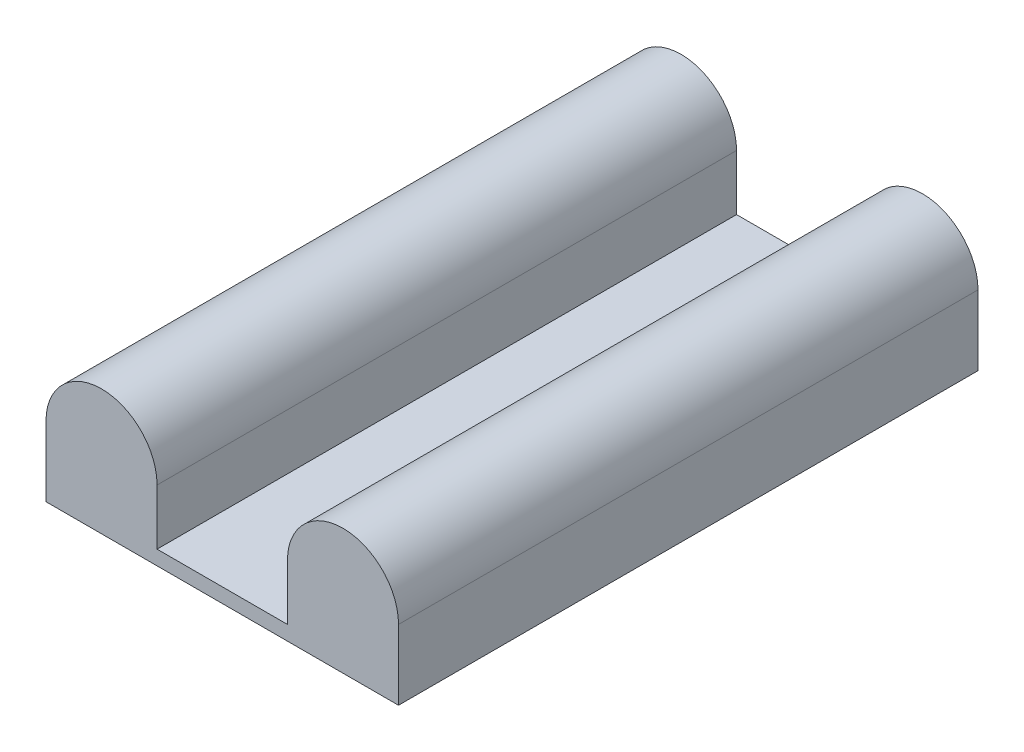
SolidWorks part; units mm, degrees
ref_plane "Front Plane" through (0, 0, 0) normal (0, 0, 1) x (1, 0, 0)
ref_plane "Top Plane" through (0, 0, 0) normal (0, 1, 0) x (1, 0, 0)
ref_plane "Right Plane" through (0, 0, 0) normal (1, 0, 0) x (0, 0, -1)
sketch "Sketch1" plane through (0, 0, 0) normal (0, 0, 1) x (1, 0, 0)
  line L0 (-11.5, 0) -> (61.5, 0)
  line L1 (61.5, 0) -> (61.5, -11.5)
  line L2 (61.5, -11.5) -> (-11.5, -11.5)
  line L3 (-11.5, -11.5) -> (-11.5, 0)
  line L4 (38.5, 0) -> (38.5, -11.5)
  line L5 (-11.5, 0) -> (11.5, 0)
  line L6 (-11.5, 0) -> (-11.5, -11.5)
  line L7 (-11.5, -11.5) -> (11.5, -11.5)
  line L8 (11.5, 0) -> (11.5, -11.5)
  line L10 (-11.5, -11.5) -> (61.5, -11.5)
  line L11 (-11.5, -11.5) -> (-11.5, -14.5)
  line L12 (-11.5, -14.5) -> (61.5, -14.5)
  line L13 (61.5, -11.5) -> (61.5, -14.5)
  circle A0 centre (0, 0) radius 11.5
  circle A1 centre (50, 0) radius 11.5
  dimension "D1" = 23
  dimension "D2" = 23
  dimension "D3" = 73
  dimension "D4" = 3
extrude "Boss-Extrude1" add sketch "Sketch1" along normal blind 120 contours L0 A0 | L0 A0 | A0 L2 L8 | A0 L3 L7 | A1 L4 L2 | L0 A1 | L0 A1 | A1 L2 L1 | L11 L10 L13 L12
